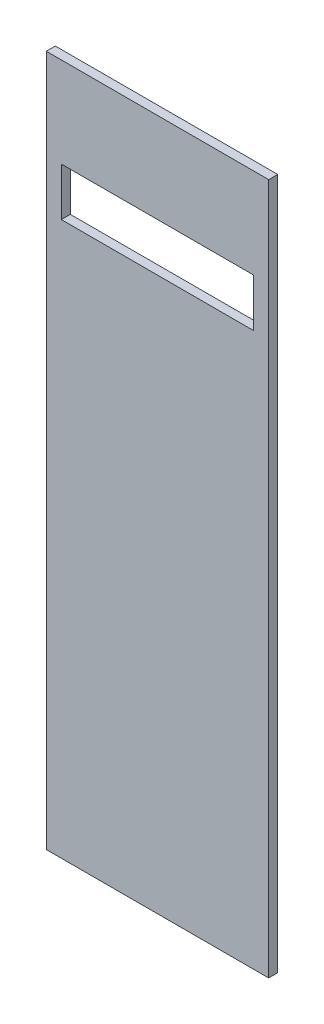
SolidWorks part; units mm, degrees
ref_plane "Plano frontal" through (0, 0, 0) normal (0, 0, 1) x (1, 0, 0)
ref_plane "Plano superior" through (0, 0, 0) normal (0, 1, 0) x (1, 0, 0)
ref_plane "Plano direito" through (0, 0, 0) normal (1, 0, 0) x (0, 0, -1)
sketch "Esboço1" plane through (0, 0, 0) normal (0, 0, 1) x (1, 0, 0)
  line L1 (-185, 575) -> (185, 575)
  line L2 (-185, 575) -> (-185, -575)
  line L3 (-185, -575) -> (185, -575)
  line L4 (185, 575) -> (185, -575)
  line L5 (-185, 575) -> (185, -575) construction
  line L6 (-185, -575) -> (185, 575) construction
  point P0 (0, 0)
  dimension "D1" = 370
  dimension "D2" = 1150
extrude "Ressalto-extrusão1" add sketch "Esboço1" along normal blind 15
sketch "Esboço2" plane through (0, 0, 15) normal (0, 0, 1) x (1, 0, 0)
  line L0 (-185, 575) -> (-185, -575) construction
  line L1 (-160, 425) -> (160, 425)
  line L2 (-160, 425) -> (-160, 345)
  line L3 (-160, 345) -> (160, 345)
  line L4 (160, 425) -> (160, 345)
  line L5 (-160, 425) -> (160, 345) construction
  line L6 (-160, 345) -> (160, 425) construction
  line L7 (185, 575) -> (-185, 575) construction
  point P0 (0, 385)
  dimension "D1" = 320
  dimension "D2" = 185
  dimension "D3" = 80
  dimension "D4" = 150
  dimension "D5" = 25
extrude "Corte-extrusão1" cut sketch "Esboço2" against normal blind 15
